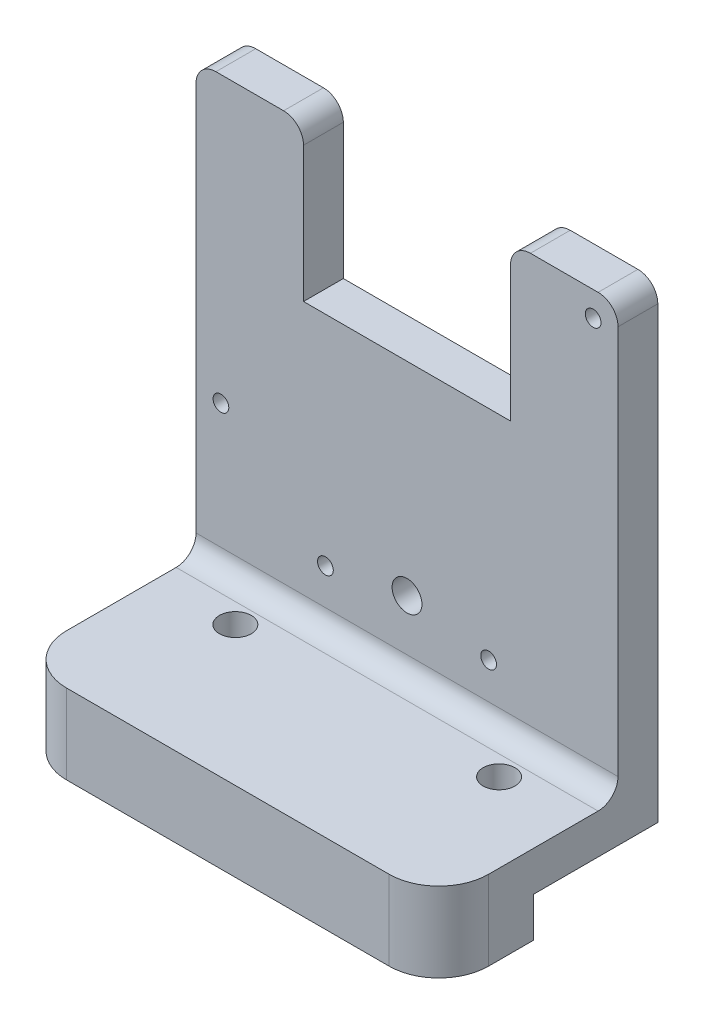
SolidWorks part; units mm, degrees
ref_plane "Front Plane" through (0, 0, 0) normal (0, 0, 1) x (1, 0, 0)
ref_plane "Top Plane" through (0, 0, 0) normal (0, 1, 0) x (1, 0, 0)
ref_plane "Right Plane" through (0, 0, 0) normal (1, 0, 0) x (0, 0, -1)
sketch "Sketch1" plane through (0, 0, 0) normal (1, 0, 0) x (0, 0, -1)
  line L0 (-10.795, -34.4678) -> (5.08, -34.4678)
  line L1 (0, 25.4) -> (5.08, 25.4)
  line L2 (0, 25.4) -> (0, -29.3878)
  line L3 (-22.86, -29.3878) -> (-22.86, -39.5478)
  line L4 (5.08, -34.4678) -> (5.08, 25.4)
  line L11 (-22.86, -39.5478) -> (-10.795, -39.5478)
  line L12 (-10.795, -34.4678) -> (-10.795, -39.5478)
  line L13 (0, -29.3878) -> (-22.86, -29.3878)
  dimension "D1" = 12.065
  dimension "D2" = 5.08
  dimension "D3" = 5.08
  dimension "D4" = 10.16
  dimension "D5" = 15.875
  dimension "D6" = 59.8678
  dimension "D7" = 25.4
extrude "Boss-Extrude1" add sketch "Sketch1" along normal mid plane 53.848
sketch "Sketch2" plane through (0, 0, 0) normal (0, 0, 1) x (1, 0, 0)
  line L0 (-26.924, 25.4) -> (-26.924, -29.3878) construction
  line L1 (26.924, 25.4) -> (26.924, -29.3878) construction
  line L2 (26.924, 25.4) -> (-26.924, 25.4) construction
  line L3 (0, -34.4678) -> (0, 25.4) construction
  circle A1 centre (23.749, 22.225) radius 1.0033
  circle A2 centre (-10.414, -22.225) radius 1.0033
  circle A3 centre (10.414, -22.225) radius 1.0033
  circle A4 centre (0, -20.32) radius 1.905
  circle A5 centre (-23.749, -10.922) radius 1.0033
  dimension "D3" = 2.0066
  dimension "D6" = 3.175
  dimension "D7" = 44.45
  dimension "D8" = 45.72
  dimension "D9" = 3.81
  dimension "D1" = 16.51
  dimension "D2" = 16.51
  dimension "D10" = 36.322
extrude "Cut-Extrude1" cut sketch "Sketch2" against normal blind 51.308
sketch "Sketch3" plane through (0, 0, 0) normal (0, 0, 1) x (1, 0, 0)
  line L0 (26.924, 25.4) -> (-26.924, 25.4) construction
  line L1 (-13.208, 25.4) -> (13.208, 25.4)
  line L2 (-13.208, 25.4) -> (-13.208, 5.588)
  line L3 (-13.208, 5.588) -> (13.208, 5.588)
  line L4 (13.208, 25.4) -> (13.208, 5.588)
  line L5 (-26.924, 25.4) -> (-26.924, -29.3878) construction
  line L6 (26.924, 25.4) -> (26.924, -29.3878) construction
  dimension "D1" = 13.716
  dimension "D2" = 13.716
  dimension "D3" = 19.812
extrude "Cut-Extrude2" cut sketch "Sketch3" against normal blind 5.08
fillet "Fillet1" radius 6.35 2 edges at (-26.924, -34.4678, 22.86) (26.924, -34.4678, 22.86)
fillet "Fillet2" radius 2.54 4 edges at (26.924, 25.4, -2.54) (13.208, 25.4, -2.54) (-26.924, 25.4, -2.54) (-13.208, 25.4, -2.54)
fillet "Fillet3" radius 2.54 1 edges at (0, -29.3878, 0)
sketch "Sketch4" plane through (0, -29.3878, 0) normal (0, 1, 0) x (1, 0, 0)
  line L0 (20.574, -22.86) -> (-20.574, -22.86) construction
  circle A0 centre (-16.8275, -5.08) radius 2.032
  circle A1 centre (16.8275, -5.08) radius 2.032
  dimension "D4" = 4.064
  dimension "D1" = 16.8275
  dimension "D2" = 16.8275
  dimension "D3" = 17.78
extrude "Cut-Extrude3" cut sketch "Sketch4" against normal through all
